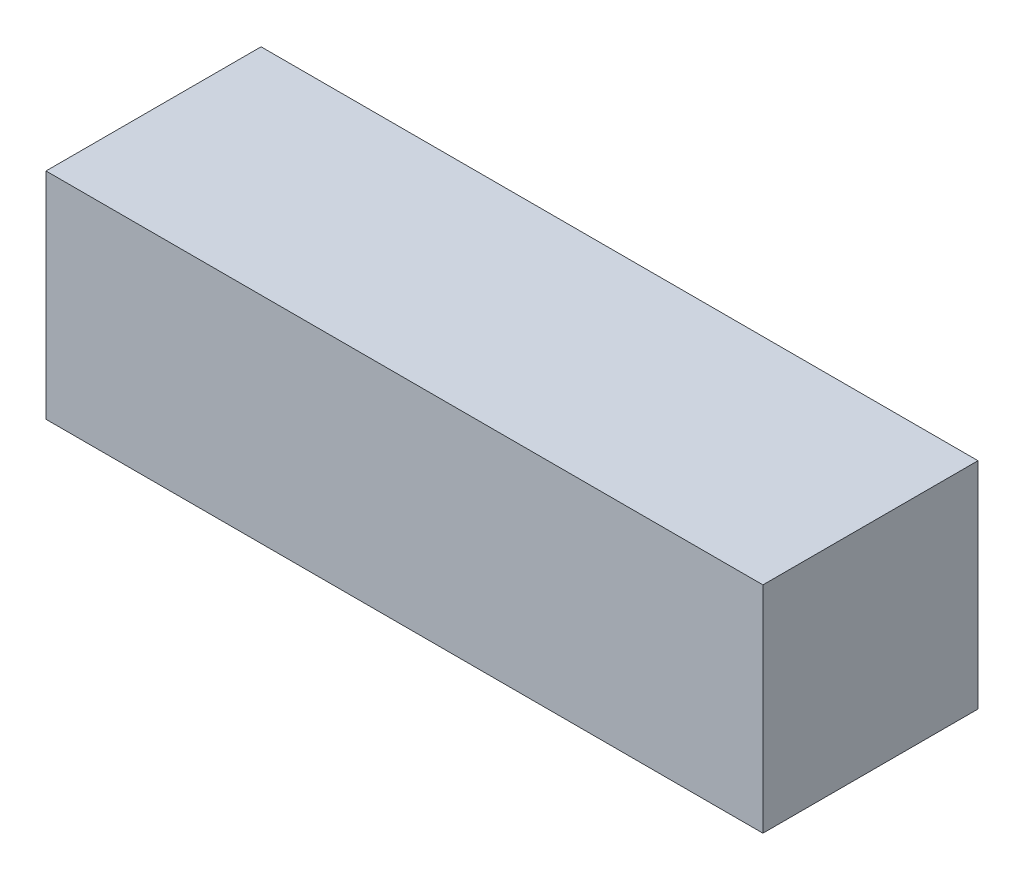
SolidWorks part; units mm, degrees
material "Pine"
ref_plane "Front Plane" through (0, 0, 0) normal (0, 0, 1) x (1, 0, 0)
ref_plane "Top Plane" through (0, 0, 0) normal (0, 1, 0) x (1, 0, 0)
ref_plane "Right Plane" through (0, 0, 0) normal (1, 0, 0) x (0, 0, -1)
sketch "Sketch1" plane through (0, 0, 0) normal (1, 0, 0) x (0, 0, -1)
  line L1 (19.05, -19.05) -> (-19.05, -19.05)
  line L2 (19.05, -19.05) -> (19.05, 19.05)
  line L3 (19.05, 19.05) -> (-19.05, 19.05)
  line L4 (-19.05, -19.05) -> (-19.05, 19.05)
  line L5 (19.05, -19.05) -> (-19.05, 19.05) construction
  line L6 (19.05, 19.05) -> (-19.05, -19.05) construction
  point P0 (0, 0)
  dimension "D1" = 38.1
  dimension "D2" = 38.1
extrude "Boss-Extrude1" add sketch "Sketch1" along normal blind 127 contours L4 L3 L2 L1
